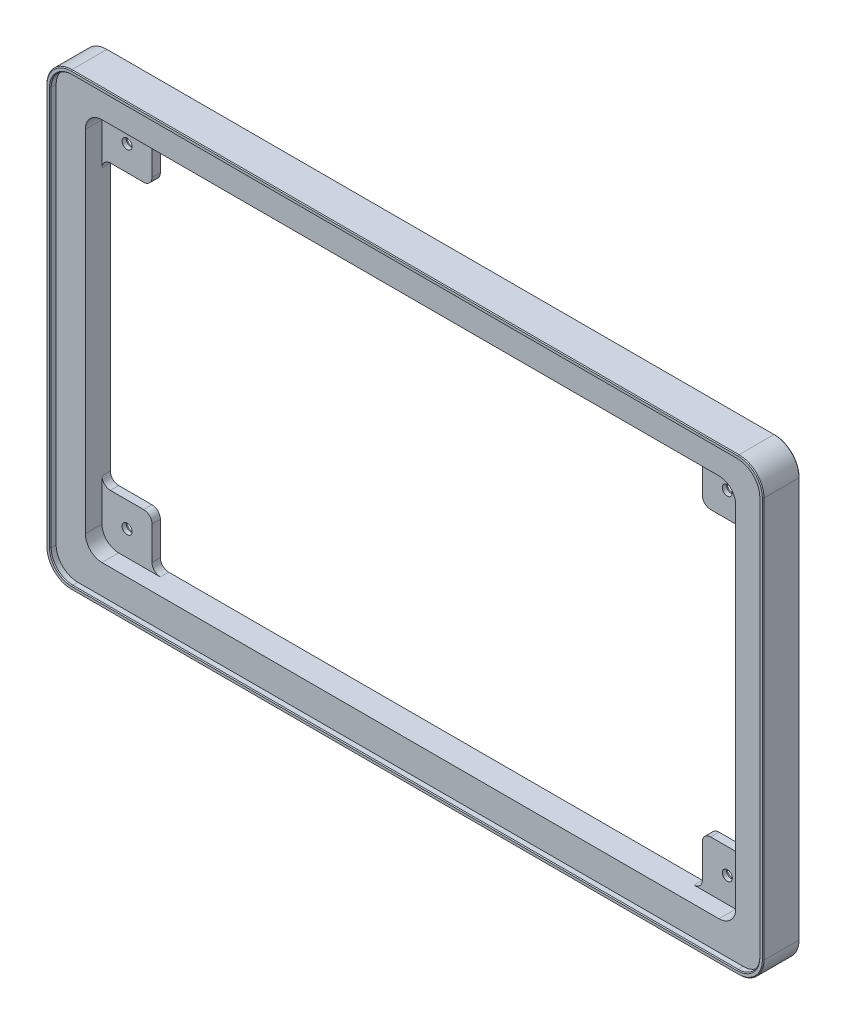
SolidWorks part; units mm, degrees
ref_plane "Спереди" through (0, 0, 0) normal (0, 0, 1) x (1, 0, 0)
ref_plane "Сверху" through (0, 0, 0) normal (0, 1, 0) x (1, 0, 0)
ref_plane "Справа" through (0, 0, 0) normal (1, 0, 0) x (0, 0, -1)
sketch "Эскиз1" plane through (0, 0, 0) normal (0, 0, 1) x (1, 0, 0)
  line L1 (-40, 27) -> (40, 27)
  line L2 (-43, 24) -> (-43, -24)
  line L3 (-40, -27) -> (40, -27)
  line L4 (43, 24) -> (43, -24)
  line L5 (-43, 27) -> (43, -27) construction
  line L6 (-43, -27) -> (43, 27) construction
  arc A0 (-43, -24) -> (-40, -27) centre (-40, -24) ccw
  arc A1 (40, -27) -> (43, -24) centre (40, -24) ccw
  arc A2 (40, 27) -> (43, 24) centre (40, 24) cw
  arc A3 (-40, 27) -> (-43, 24) centre (-40, 24) ccw
  point P0 (0, 0)
  dimension "D3" = 3
  dimension "D1" = 86
  dimension "D2" = 54
extrude "Бобышка-Вытянуть1" add sketch "Эскиз1" along normal blind 4.4
sketch "Эскиз2" plane through (0, 0, 4.4) normal (0, 0, 1) x (1, 0, 0)
  line L0 (0, 27) -> (0, -27) construction
  line L1 (40, 27) -> (-40, 27) construction
  line L2 (-40, -27) -> (40, -27) construction
  line L3 (43, -24) -> (43, 24) construction
  line L4 (-39.9, 26.5) -> (39.9, 26.5)
  line L5 (-42.5, 23.9) -> (-42.5, -23.9)
  line L6 (-39.9, -26.5) -> (39.9, -26.5)
  line L7 (42.5, 23.9) -> (42.5, -23.9)
  line L8 (-42.5, 26.5) -> (42.5, -26.5) construction
  line L9 (-42.5, -26.5) -> (42.5, 26.5) construction
  arc A0 (-39.9, 26.5) -> (-42.5, 23.9) centre (-39.9, 23.9) ccw
  arc A1 (-42.5, -23.9) -> (-39.9, -26.5) centre (-39.9, -23.9) ccw
  arc A2 (39.9, -26.5) -> (42.5, -23.9) centre (39.9, -23.9) ccw
  arc A3 (39.9, 26.5) -> (42.5, 23.9) centre (39.9, 23.9) cw
  point P6 (0, 0)
  dimension "D1" = 2.6
  dimension "D2" = 0.5
  dimension "D3" = 0.5
extrude "Вырез-Вытянуть1" cut sketch "Эскиз2" against normal blind 4.4
sketch "Эскиз4" plane through (0, 0, 4.4) normal (0, 0, 1) x (1, 0, 0)
  line L0 (-39.9, 26.5) -> (39.9, 26.5)
  line L7 (-39.9, -26.5) -> (39.9, -26.5)
  line L8 (42.5, 23.9) -> (42.5, -23.9)
  line L9 (-42.5, 23.9) -> (-42.5, -23.9)
  arc A0 (-42.5, 23.9) -> (-39.9, 26.5) centre (-39.9, 23.9) cw
  arc A1 (42.5, 23.9) -> (39.9, 26.5) centre (39.9, 23.9) ccw
  arc A2 (42.5, 23.9) -> (39.9, 26.5) centre (39.9, 23.9) ccw construction
  arc A3 (42.5, -23.9) -> (39.9, -26.5) centre (39.9, -23.9) cw
  arc A4 (-39.9, -26.5) -> (-42.5, -23.9) centre (-39.9, -23.9) cw
extrude "Бобышка-Вытянуть2" add sketch "Эскиз4" against normal blind 3 from offset 0.7 offset against normal yes
sketch "Эскиз5" plane through (0, 0, 3.7) normal (0, 0, 1) x (1, 0, 0)
  line L0 (43, -24) -> (43, 24) construction
  line L1 (-37, 23) -> (37, 23)
  line L2 (-39, 21) -> (-39, -21)
  line L3 (-37, -23) -> (37, -23)
  line L4 (39, 21) -> (39, -21)
  line L5 (-39, 23) -> (39, -23) construction
  line L6 (-39, -23) -> (39, 23) construction
  line L7 (40, 27) -> (-40, 27) construction
  arc A0 (37, -23) -> (39, -21) centre (37, -21) ccw
  arc A1 (-39, -21) -> (-37, -23) centre (-37, -21) ccw
  arc A2 (-37, 23) -> (-39, 21) centre (-37, 21) ccw
  arc A3 (37, 23) -> (39, 21) centre (37, 21) cw
  point P0 (0, 0)
  dimension "D3" = 2
  dimension "D1" = 4
  dimension "D2" = 4
extrude "Вырез-Вытянуть2" cut sketch "Эскиз5" against normal blind 3
sketch "Эскиз7" plane through (0, 0, 0.7) normal (0, 0, -1) x (-1, 0, 0)
  line L0 (-37, 23) -> (37, 23) construction
  line L1 (-39, 23) -> (-33, 23)
  line L2 (-39, 23) -> (-39, 17)
  line L3 (-39, 17) -> (-33, 17)
  line L4 (-33, 23) -> (-33, 17)
  line L5 (-39, -21) -> (-39, 21) construction
  line L6 (39, 21) -> (39, -21) construction
  line L7 (39, 23) -> (33, 23)
  line L8 (39, 23) -> (39, 17)
  line L9 (39, 17) -> (33, 17)
  line L10 (33, 23) -> (33, 17)
  line L11 (39, -23) -> (33, -23)
  line L12 (39, -23) -> (39, -17)
  line L13 (39, -17) -> (33, -17)
  line L14 (33, -23) -> (33, -17)
  line L15 (-39, -23) -> (-33, -23)
  line L16 (-39, -23) -> (-39, -17)
  line L17 (-39, -17) -> (-33, -17)
  line L18 (-33, -23) -> (-33, -17)
  line L19 (37, -23) -> (-37, -23) construction
  dimension "D1" = 6
extrude "Бобышка-Вытянуть4" add sketch "Эскиз7" against normal blind 1
fillet "Скругление1" radius 1 12 edges at (-33, -23, 1.2) (-33, -17, 1.2) (-39, -17, 1.2) (33, -23, 1.2) (33, -17, 1.2) (39, -17, 1.2) (39, 17, 1.2) (33, 17, 1.2) (33, 23, 1.2) (-33, 17, 1.2) (-33, 23, 1.2) (-39, 17, 1.2)
sketch "Эскиз8" plane through (0, 0, 0.7) normal (0, 0, -1) x (-1, 0, 0)
  line L0 (-33, -22) -> (-33, -18) construction
  line L1 (-36, 20) -> (36, 20) construction
  line L2 (-36, 20) -> (-36, -20) construction
  line L3 (-36, -20) -> (36, -20) construction
  line L4 (36, 20) -> (36, -20) construction
  line L5 (-36, 20) -> (36, -20) construction
  line L6 (-36, -20) -> (36, 20) construction
  line L7 (-34, -17) -> (-38, -17) construction
  circle A0 centre (-36, 20) radius 0.6
  circle A1 centre (36, 20) radius 0.6
  circle A2 centre (36, -20) radius 0.6
  circle A3 centre (-36, -20) radius 0.6
  point P0 (0, 0)
  dimension "D3" = 1.2
  dimension "D1" = 3
  dimension "D2" = 3
extrude "Вырез-Вытянуть3" cut sketch "Эскиз8" against normal blind 1
chamfer "Фаска1" distance 0.1 angle 45 32 edges at (0, -27, 0) (42.1213, -26.1213, 0) (-42.1213, -26.1213, 0) (43, 0, 0) (-43, 0, 0) (42.1213, 26.1213, 0) (-42.1213, 26.1213, 0) (0, 27, 0) (0, -26.5, 0) (41.7385, -25.7385, 0) (-41.7385, -25.7385, 0) (42.5, 0, 0) (-42.5, 0, 0) (41.7385, 25.7385, 0) (-41.7385, 25.7385, 0) (0, 26.5, 0) (-42.1213, -26.1213, 4.4) (0, -27, 4.4) (-43, 0, 4.4) (42.1213, -26.1213, 4.4) (-42.1213, 26.1213, 4.4) (43, 0, 4.4) (0, 27, 4.4) (42.1213, 26.1213, 4.4) (-41.7385, -25.7385, 4.4) (0, -26.5, 4.4) (-42.5, 0, 4.4) (41.7385, -25.7385, 4.4) (-41.7385, 25.7385, 4.4) (42.5, 0, 4.4) (0, 26.5, 4.4) (41.7385, 25.7385, 4.4)
sketch "Эскиз9" plane through (0, 0, 0.7) normal (0, 0, -1) x (-1, 0, 0)
  circle A0 centre (36, 20) radius 1.1
  circle A1 centre (36, -20) radius 1.1
  circle A2 centre (-36, -20) radius 1.1
  circle A3 centre (-36, 20) radius 1.1
  dimension "D1" = 2.2
extrude "Вырез-Вытянуть4" cut sketch "Эскиз9" against normal blind 0.5
